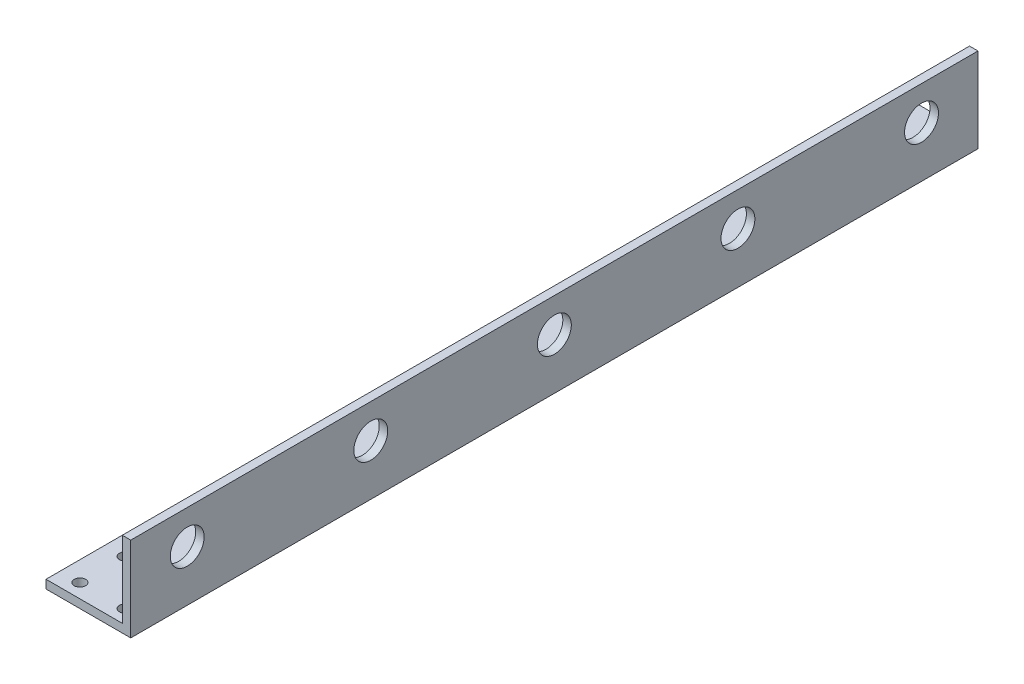
SolidWorks part; units mm, degrees
ref_plane "Front" through (0, 0, 0) normal (0, 0, 1) x (1, 0, 0)
ref_plane "Top" through (0, 0, 0) normal (0, 1, 0) x (1, 0, 0)
ref_plane "Right" through (0, 0, 0) normal (1, 0, 0) x (0, 0, -1)
sketch "草图1" plane through (0, 0, 0) normal (0, 0, 1) x (1, 0, 0)
  line L1 (-15, -15) -> (15, -15)
  line L2 (-15, -15) -> (-15, -12)
  line L3 (12, 15) -> (15, 15)
  line L4 (15, -15) -> (15, 15)
  line L8 (12, 15) -> (12, -12)
  line L9 (-15, -12) -> (12, -12)
  point P0 (0, 0)
extrude "凸台-拉伸1" add sketch "草图1" along normal blind 300
sketch "草图2" plane through (12, 0, 0) normal (-1, 0, 0) x (0, 0, 1)
  circle A0 centre (20, 3) radius 6
  circle A1 centre (85, 3) radius 6
  circle A2 centre (150, 3) radius 6
  circle A3 centre (215, 3) radius 6
  circle A4 centre (280, 3) radius 6
  dimension "D1" = 5
extrude "切除-拉伸1" cut sketch "草图2" against normal blind 300
sketch "草图3" plane through (0, -15, 0) normal (0, -1, 0) x (1, 0, 0)
  line L0 (0, 300) -> (0, 295)
  line L2 (-15, 300) -> (15, 300) construction
  circle A0 centre (8, 5) radius 2
  circle A1 centre (-8, 5) radius 2
  circle A2 centre (-8, 21) radius 2
  circle A3 centre (8, 21) radius 2
  circle A4 centre (8, 295) radius 2
  circle A5 centre (8, 279) radius 2
  circle A6 centre (-8, 279) radius 2
  circle A7 centre (-8, 295) radius 2
  point P21 (0, 13)
  point P30 (0, 287)
  dimension "D1" = 4
  dimension "D2" = 4
extrude "切除-拉伸2" cut sketch "草图3" against normal blind 300 contours A7 | A6 | A5 | A4 | A2 | A1 | A0 | A3
